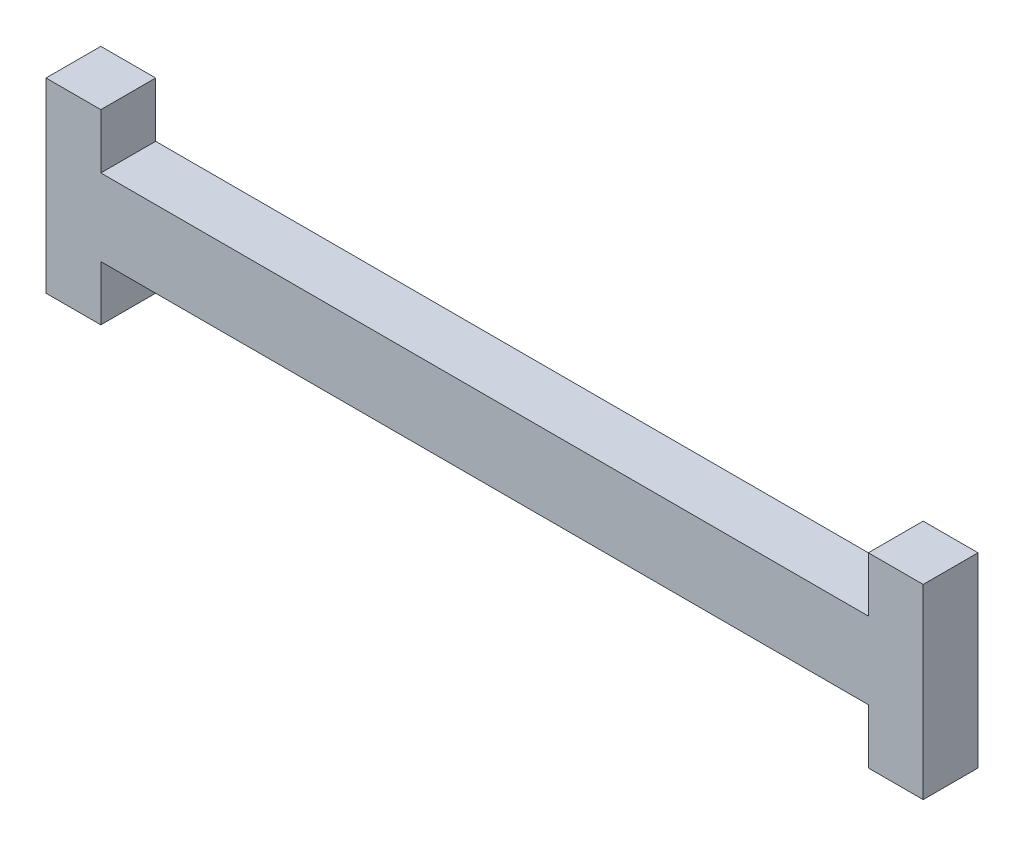
SolidWorks part; units mm, degrees
material "Balsa"
ref_plane "Plan de face" through (0, 0, 0) normal (0, 0, 1) x (1, 0, 0)
ref_plane "Plan de dessus" through (0, 0, 0) normal (0, 1, 0) x (1, 0, 0)
ref_plane "Plan de droite" through (0, 0, 0) normal (1, 0, 0) x (0, 0, -1)
sketch "Esquisse1" plane through (0, 0, 0) normal (0, 0, 1) x (1, 0, 0)
  line L0 (121.1746, 222.4211) -> (126.1746, 222.4211)
  line L1 (126.1746, 222.4211) -> (126.1746, 217.4211)
  line L2 (126.1746, 217.4211) -> (196.1746, 217.4211)
  line L3 (121.1746, 222.4211) -> (121.1746, 205.4211)
  line L4 (121.1746, 205.4211) -> (126.1746, 205.4211)
  line L5 (126.1746, 205.4211) -> (126.1746, 210.4211)
  line L6 (126.1746, 210.4211) -> (196.1746, 210.4211)
  line L7 (161.1746, 222.4211) -> (161.1746, 205.4211) construction
  line L8 (196.1746, 205.4211) -> (196.1746, 210.4211)
  line L9 (201.1746, 205.4211) -> (196.1746, 205.4211)
  line L10 (201.1746, 222.4211) -> (201.1746, 205.4211)
  line L11 (196.1746, 222.4211) -> (196.1746, 217.4211)
  line L12 (201.1746, 222.4211) -> (196.1746, 222.4211)
  dimension "D1" = 5
  dimension "D2" = 80
  dimension "D3" = 7
  dimension "D4" = 5
  dimension "D5" = 5
extrude "Boss.-Extru.1" add sketch "Esquisse1" against normal blind 5
